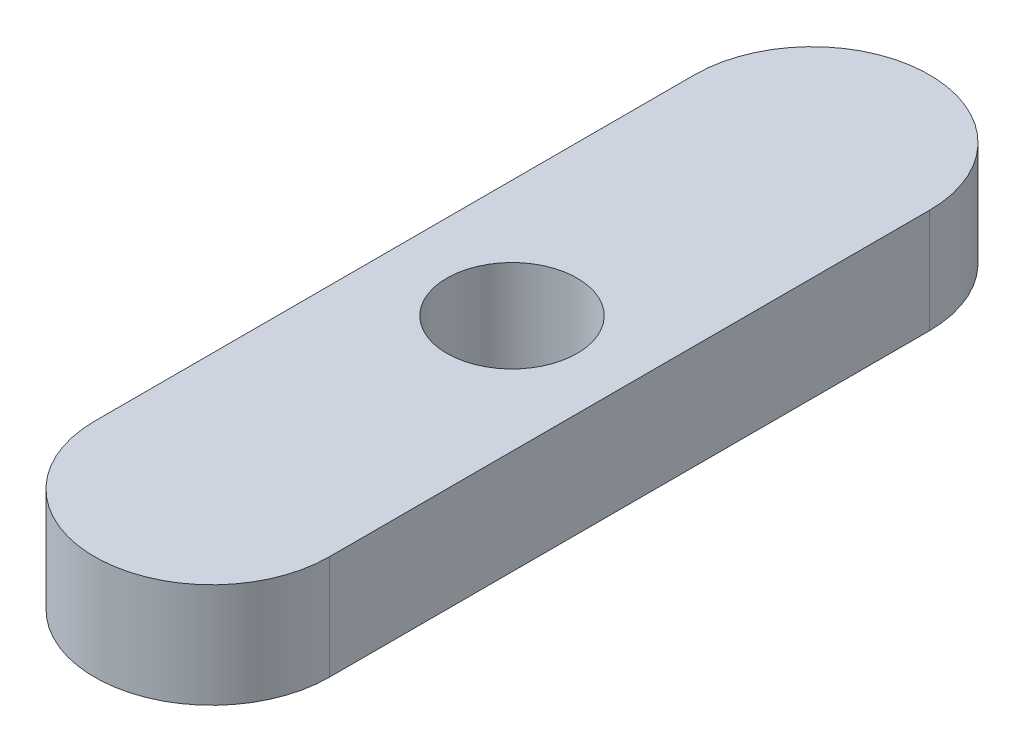
SolidWorks part; units mm, degrees
ref_plane "Front Plane" through (0, 0, 0) normal (0, 0, 1) x (1, 0, 0)
ref_plane "Top Plane" through (0, 0, 0) normal (0, 1, 0) x (1, 0, 0)
ref_plane "Right Plane" through (0, 0, 0) normal (1, 0, 0) x (0, 0, -1)
sketch "Sketch1" plane through (0, 0, 0) normal (0, 1, 0) x (1, 0, 0)
  line L0 (-2.25, 0) -> (-2.25, 11.5)
  line L1 (2.25, 11.5) -> (2.25, 0)
  line L2 (0, -2.25) -> (8, -2.25) construction
  line L3 (8, -2.25) -> (8, 13.75) construction
  line L4 (0, 13.75) -> (8, 13.75) construction
  arc A2 (-2.25, 0) -> (2.25, 0) centre (0, 0) ccw
  arc A3 (2.25, 11.5) -> (-2.25, 11.5) centre (0, 11.5) ccw
  circle A4 centre (0, 5.75) radius 1
  point P13 (-2.25, 5.75)
  dimension "D1" = 16
  dimension "D2" = 8
  dimension "D3" = 4.5
  dimension "D4" = 2
extrude "Boss-Extrude1" add sketch "Sketch1" along normal blind 2
other "Move Face1" face at (0, 2, -4.75) parameters "D1"=0.25
